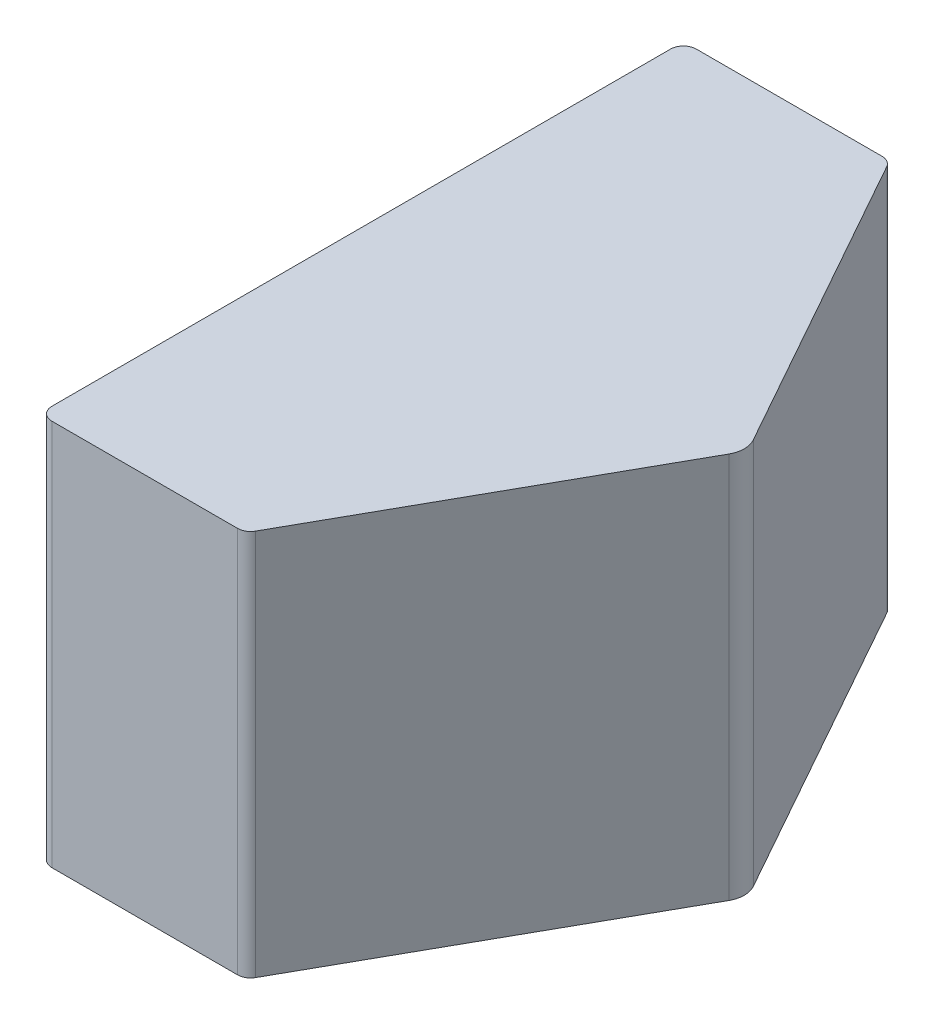
SolidWorks part; units mm, degrees
ref_plane "前视基准面" through (0, 0, 0) normal (0, 0, 1) x (1, 0, 0)
ref_plane "上视基准面" through (0, 0, 0) normal (0, 1, 0) x (1, 0, 0)
ref_plane "右视基准面" through (0, 0, 0) normal (1, 0, 0) x (0, 0, -1)
sketch "草图1" plane through (0, 0, 0) normal (0, 1, 0) x (1, 0, 0)
  line L0 (0, -5) -> (0, -245)
  line L5 (5, 0) -> (77.0694, 0)
  line L6 (5, -250) -> (77.0694, -250)
  line L7 (80, 0) -> (80, -250) construction
  line L8 (0, -125) -> (150, -125) construction
  line L9 (81.4319, -2.557) -> (147.3518, -120.2711)
  line L10 (147.3518, -129.7289) -> (81.4319, -247.443)
  arc A0 (147.3518, -129.7289) -> (147.3518, -120.2711) centre (138.9073, -125) ccw
  arc A1 (0, -245) -> (5, -250) centre (5, -245) ccw
  arc A2 (81.4319, -247.443) -> (77.0694, -250) centre (77.0694, -245) cw
  arc A3 (77.0694, 0) -> (81.4319, -2.557) centre (77.0694, -5) cw
  arc A4 (0, -5) -> (5, 0) centre (5, -5) cw
  point P4 (80, -180.3029)
  point P13 (0, -250)
  point P22 (0, 0)
  dimension "D4" = 9.6784
  dimension "D5" = 5
  dimension "D1" = 250
  dimension "D2" = 80
  dimension "D3" = 150
extrude "凸台-拉伸1" add sketch "草图1" along normal blind 150
sketch "草图2" plane through (0, 0, 0) normal (-1, 0, 0) x (0, 0, 1)
  line L0 (125, 150) -> (125, 0) construction
  line L1 (5, 150) -> (245, 150) construction
  line L2 (5, 0) -> (245, 0) construction
  line L3 (85, 80) -> (165, 80)
  line L4 (85, 80) -> (85, 0)
  line L5 (165, 80) -> (165, 0)
  line L6 (85, 0) -> (165, 0)
  line L7 (85, 80) -> (165, 0) construction
  line L8 (165, 80) -> (85, 0) construction
  point P6 (125, 40.2208)
  point P7 (125, 40)
  point P8 (125, 45.3036)
  dimension "D1" = 80
  dimension "D2" = 80
extrude "切除-拉伸1" cut sketch "草图2" against normal blind 100
